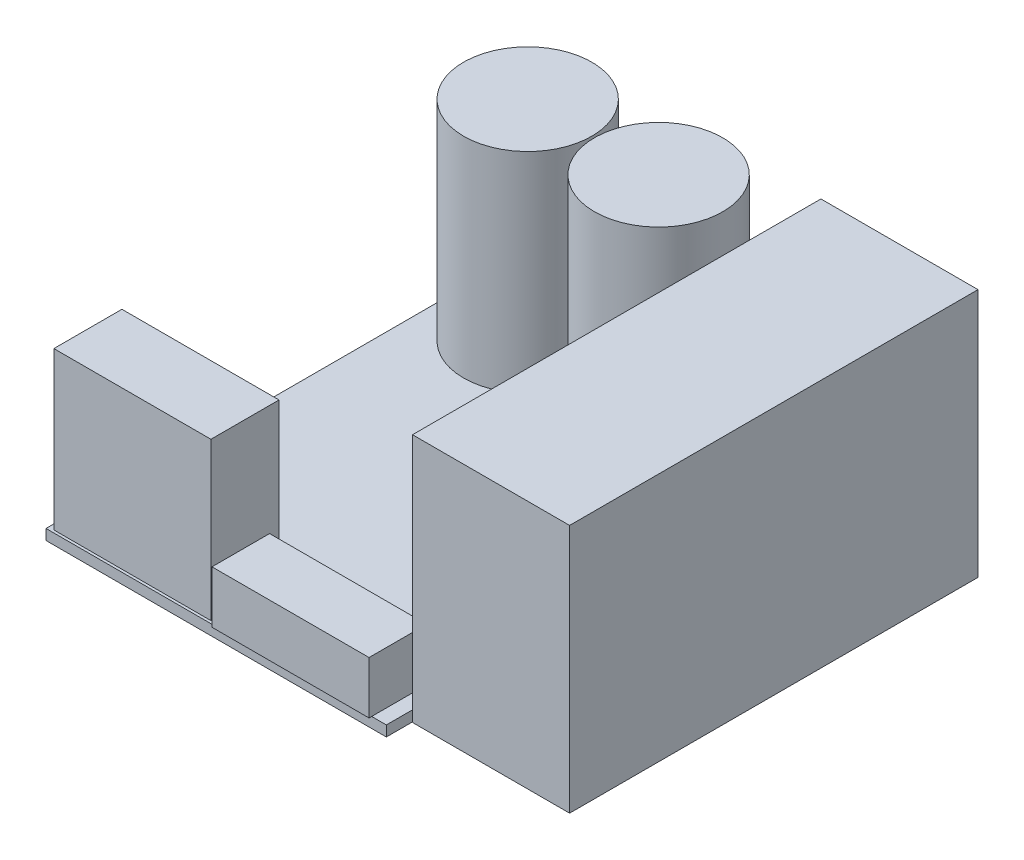
SolidWorks part; units mm, degrees
ref_plane "Front Plane" through (0, 0, 0) normal (0, 0, 1) x (1, 0, 0)
ref_plane "Top Plane" through (0, 0, 0) normal (0, 1, 0) x (1, 0, 0)
ref_plane "Right Plane" through (0, 0, 0) normal (1, 0, 0) x (0, 0, -1)
sketch "Sketch1" plane through (0, 0, 0) normal (0, 1, 0) x (1, 0, 0)
  line L0 (194.8333, 372) -> (194.8333, -184.8417) construction
  line L1 (0, 0) -> (65, 0)
  line L2 (0, 0) -> (0, -98)
  line L3 (0, -98) -> (65, -98)
  line L4 (65, 0) -> (65, -98)
  line L6 (54.3872, -37.1089) -> (60.0909, -37.1089)
  line L7 (54.3872, -37.1089) -> (54.3872, -44.9394)
  line L8 (54.3872, -44.9394) -> (60.0909, -44.9394)
  line L9 (60.0909, -37.1089) -> (60.0909, -44.9394)
  line L10 (54.3872, -66.6905) -> (60.0909, -66.6905)
  line L11 (54.3872, -66.6905) -> (54.3872, -74.811)
  line L12 (54.3872, -74.811) -> (60.0909, -74.811)
  line L13 (60.0909, -66.6905) -> (60.0909, -74.811)
  circle A0 centre (4.8, -5.4) radius 1.75
  circle A1 centre (59.2, -10.8) radius 1.75
  circle A2 centre (19.5, -80) radius 1.75
  circle A3 centre (47.5, -80.1) radius 1.75
  dimension "D3" = 3.5
  dimension "D6" = 3.5
  dimension "D9" = 3.5
  dimension "D12" = 3.5
  dimension "D1" = 65
  dimension "D2" = 98
  dimension "D4" = 5.4
  dimension "D5" = 4.8
  dimension "D7" = 5.8
  dimension "D8" = 10.8
  dimension "D10" = 19.5
  dimension "D11" = 18
  dimension "D13" = 17.9
  dimension "D14" = 17.5
extrude "Boss-Extrude1" add sketch "Sketch1" along normal blind 2
sketch "Sketch2" plane through (0, 2, 0) normal (0, 1, 0) x (1, 0, 0)
  line L0 (65, 0) -> (0, 0) construction
  line L1 (13.5, 2) -> (28.5, 2)
  line L2 (13.5, 2) -> (13.5, -4)
  line L3 (13.5, -4) -> (28.5, -4)
  line L4 (28.5, 2) -> (28.5, -4)
  line L5 (65, -98) -> (65, 0) construction
  dimension "D1" = 2
  dimension "D2" = 15
  dimension "D3" = 6
  dimension "D4" = 36.5
extrude "Boss-Extrude2" add sketch "Sketch2" along normal blind 10
sketch "Sketch3" plane through (0, 2, 0) normal (0, 1, 0) x (1, 0, 0)
  line L0 (0, 0) -> (0, -98) construction
  line L1 (65, 0) -> (28.5, 0) construction
  line L2 (13.5, 0) -> (0, 0) construction
  circle A0 centre (15, -21) radius 12.25
  circle A1 centre (40, -21) radius 12.25
  dimension "D1" = 24.5
  dimension "D2" = 24.5
  dimension "D3" = 15
  dimension "D4" = 25
  dimension "D5" = 21
  dimension "D6" = 21
extrude "Boss-Extrude3" add sketch "Sketch3" along normal blind 40
sketch "Sketch4" plane through (0, 2, 0) normal (0, 1, 0) x (1, 0, 0)
  line L0 (0, -98) -> (65, -98) construction
  line L1 (1, -84.5) -> (31, -84.5)
  line L2 (1, -84.5) -> (1, -97.5)
  line L3 (1, -97.5) -> (31, -97.5)
  line L4 (31, -84.5) -> (31, -97.5)
  line L5 (0, 0) -> (0, -98) construction
  dimension "D1" = 30
  dimension "D2" = 13
  dimension "D3" = 0.5
  dimension "D4" = 1
extrude "Boss-Extrude4" add sketch "Sketch4" along normal blind 30
sketch "Sketch5" plane through (0, 2, 0) normal (0, 1, 0) x (1, 0, 0)
  line L0 (0, -98) -> (65, -98) construction
  line L1 (32.2, -87.5) -> (62.2, -87.5)
  line L2 (32.2, -87.5) -> (32.2, -98.5)
  line L3 (32.2, -98.5) -> (62.2, -98.5)
  line L4 (62.2, -87.5) -> (62.2, -98.5)
  line L5 (31, -97.5) -> (31, -84.5) construction
  dimension "D1" = 30
  dimension "D2" = 11
  dimension "D3" = 0.5
  dimension "D4" = 1.2
extrude "Boss-Extrude5" add sketch "Sketch5" along normal blind 10
sketch "Sketch6" plane through (0, 2, 0) normal (0, 1, 0) x (1, 0, 0)
  line L0 (65, -98) -> (65, 0) construction
  line L1 (65, -15) -> (95, -15)
  line L2 (65, -15) -> (65, -93)
  line L3 (65, -93) -> (95, -93)
  line L4 (95, -15) -> (95, -93)
  line L10 (0, -98) -> (32.2, -98) construction
  dimension "D1" = 78
  dimension "D2" = 30
  dimension "D3" = 5
extrude "Boss-Extrude6" add sketch "Sketch6" along normal blind 45.5 separate body
sketch "Sketch7" plane through (0, 2, 0) normal (0, -1, 0) x (1, 0, 0)
  line L1 (65, 93) -> (95, 93)
  line L2 (65, 93) -> (65, 15)
  line L3 (65, 15) -> (95, 15)
  line L4 (95, 93) -> (95, 15)
extrude "Boss-Extrude7" add sketch "Sketch7" along normal blind 2.1
